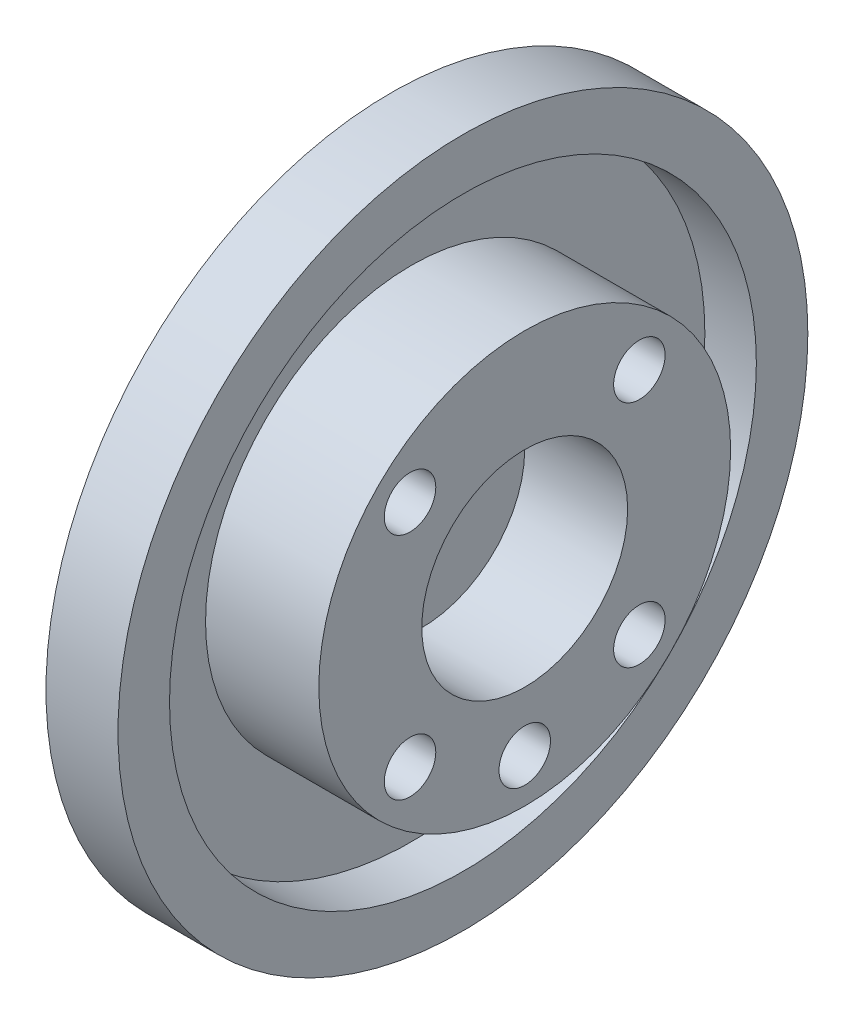
SolidWorks part; units mm, degrees
ref_plane "正面" through (0, 0, 0) normal (0, 0, 1) x (1, 0, 0)
ref_plane "平面" through (0, 0, 0) normal (0, 1, 0) x (1, 0, 0)
ref_plane "右側面" through (0, 0, 0) normal (1, 0, 0) x (0, 0, -1)
sketch "ｽｹｯﾁ1" plane through (0, 0, 0) normal (1, 0, 0) x (0, 0, -1)
  circle A0 centre (0, 0) radius 33.5
  dimension "D1" = 67
extrude "押し出し1" add sketch "ｽｹｯﾁ1" along normal blind 7
sketch "ｽｹｯﾁ3" plane through (7, 0, 0) normal (1, 0, 0) x (0, 0, -1)
  circle A0 centre (0, 0) radius 28.5
  dimension "D1" = 57
extrude "ｶｯﾄ - 押し出し1" cut sketch "ｽｹｯﾁ3" against normal blind 5
sketch "ｽｹｯﾁ4" plane through (2, 0, 0) normal (1, 0, 0) x (0, 0, -1)
  circle A0 centre (0, 0) radius 2.5
  dimension "D1" = 5
extrude "ｶｯﾄ - 押し出し2" cut sketch "ｽｹｯﾁ4" against normal blind 5
sketch "ｽｹｯﾁ5" plane through (2, 0, 0) normal (1, 0, 0) x (0, 0, -1)
  circle A0 centre (0, 0) radius 20
  dimension "D1" = 40
extrude "押し出し2" add sketch "ｽｹｯﾁ5" along normal blind 11
sketch "ｽｹｯﾁ6" plane through (13, 0, 0) normal (1, 0, 0) x (0, 0, -1)
  circle A0 centre (0, 0) radius 10
  dimension "D1" = 20
extrude "ｶｯﾄ - 押し出し5" cut sketch "ｽｹｯﾁ6" against normal blind 10
sketch "ｽｹｯﾁ7" plane through (13, 0, 0) normal (1, 0, 0) x (0, 0, -1)
  line L0 (0, 0) -> (0, 35.2217) construction
  line L1 (0, 0) -> (35.9597, 0) construction
  line L2 (22.3083, 22.3083) -> (0, 0) construction
  line L3 (12.5792, 12.5792) -> (-28.8818, -28.8818) construction
  line L4 (0, 0) -> (25.7957, -25.7957) construction
  line L5 (0, 0) -> (-25.5274, 25.5274) construction
  line L6 (0, 6.4706) -> (0, -37.3417) construction
  circle A0 centre (0, 0) radius 15.75 construction
  circle A1 centre (0, -15.7404) radius 2.5
  dimension "D1" = 31.5
  dimension "D3" = 5
  dimension "D2" = 45
hole_wizard "M5x0.8 ねじ穴1" positions "3Dｽｹｯﾁ1" profile "ｽｹｯﾁ10" tap size "M5x0.8" standard "ANSIﾒｰﾄﾙ"
sketch3d "3Dｽｹｯﾁ1"
  line L0 (13, 0, 0) -> (13, 25.5274, 25.5274) construction
  line L1 (13, 22.3083, -22.3083) -> (13, 0, 0) construction
  line L2 (13, 0, 0) -> (13, -25.7957, -25.7957) construction
  line L3 (13, 12.5792, -12.5792) -> (13, -28.8818, 28.8818) construction
  circle A0 centre (13, 0, 0) radius 15.75 construction
  point P0 (13, 11.1369, 11.1369)
  point P6 (28.75, 0, 0)
  point P7 (13, 11.1542, -11.1542)
  point P11 (13, -11.1369, -11.1369)
  point P15 (13, -11.1369, 11.1369)
  point P19 (13, 11.1369, -11.1369)
sketch "ｽｹｯﾁ10" plane through (13, 11.1369, 11.1369) normal (0, 1, 0) x (0, 0, -1)
  line L0 (0, 0) -> (0, 10.2618)
  line L1 (0, 10.2618) -> (2.1, 9)
  line L2 (2.1, 9) -> (2.1, 10)
  line L3 (2.1, 10) -> (2.5, 10)
  line L4 (2.5, 10) -> (2.5, 0)
  line L5 (2.5, 0) -> (0, 0)
  line L10 (0, 10.2618) -> (-2.1, 9) construction
  line L11 (0, -6.35) -> (0, 107.95) construction
  dimension "ねじ下穴ﾄﾞﾘﾙの直径" = 4.2
  dimension "ねじ下穴ﾄﾞﾘﾙの深さ" = 9
  dimension "ねじ山の主要直径" = 5
  dimension "ねじ山の深さ" = 10
  dimension "ﾄﾞﾘﾙ角度" = 118
extrude "ｶｯﾄ - 押し出し6" cut sketch "ｽｹｯﾁ7" against normal blind 7
